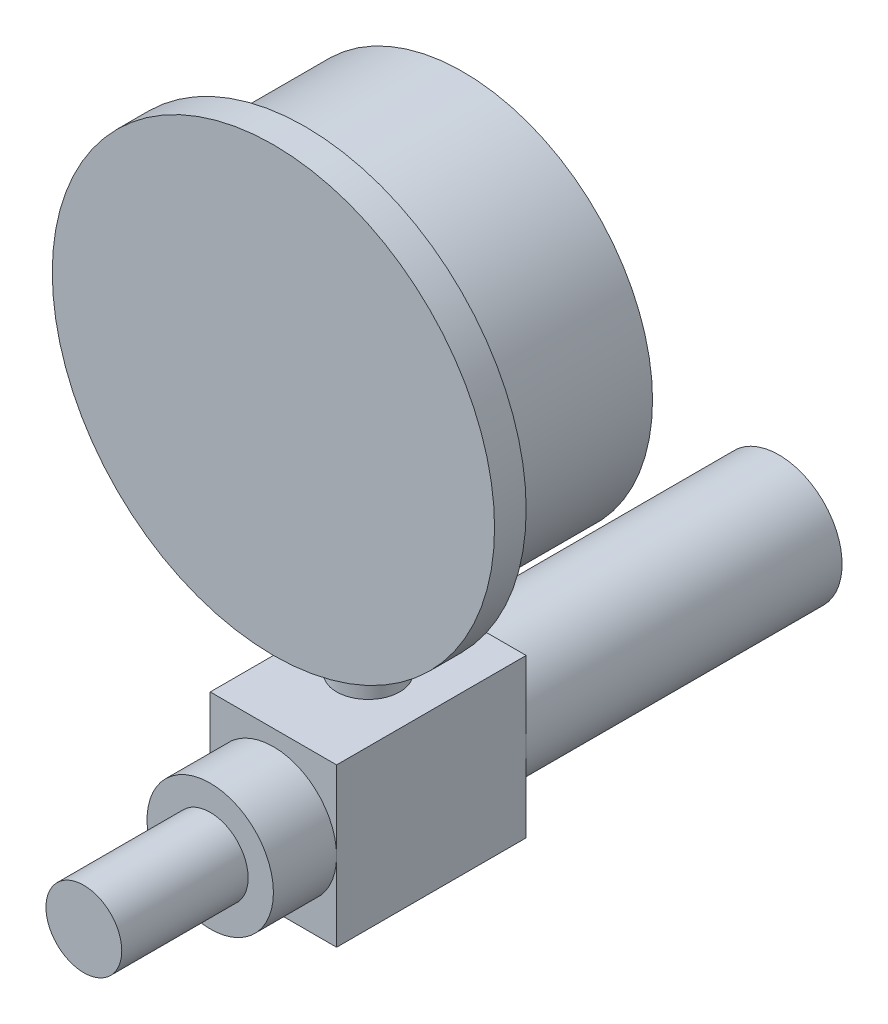
SolidWorks part; units mm, degrees
ref_plane "Alzado" through (0, 0, 0) normal (0, 0, 1) x (1, 0, 0)
ref_plane "Planta" through (0, 0, 0) normal (0, 1, 0) x (1, 0, 0)
ref_plane "Vista lateral" through (0, 0, 0) normal (1, 0, 0) x (0, 0, -1)
sketch "Croquis1" plane through (0, 0, 0) normal (0, 0, 1) x (1, 0, 0)
  line L0 (-35, 50) -> (35, 50) construction
  line L1 (35, 50) -> (35, -50) construction
  line L2 (35, -50) -> (-35, -50) construction
  line L3 (-35, -50) -> (-35, 50) construction
  line L4 (-35, 50) -> (35, -50) construction
  line L5 (-35, -50) -> (35, 50) construction
  line L7 (-10, -50) -> (10, -50)
  line L8 (-10, -50) -> (-10, -25)
  line L9 (-10, -25) -> (10, -25)
  line L10 (10, -50) -> (10, -25)
  circle A0 centre (0, 20) radius 30
  point P4 (0, 0)
  point P10 (0, -50)
  point P13 (0, 0)
  dimension "D5" = 60
  dimension "D1" = 70
  dimension "D2" = 100
  dimension "D3" = 20
  dimension "D4" = 25
extrude "Saliente-Extruir1" add sketch "Croquis1" against normal blind 30
sketch "Croquis2" plane through (0, 0, 0) normal (0, 0, 1) x (1, 0, 0)
  circle A0 centre (0, 20) radius 35
  circle A1 centre (0, 20) radius 30 construction
  circle A2 centre (0, 20) radius 30
  dimension "D1" = 70
  dimension "D2" = 60
extrude "Saliente-Extruir2" add sketch "Croquis2" against normal blind 5
sketch "Croquis3" plane through (0, -25, 0) normal (0, 1, 0) x (1, 0, 0)
  line L0 (10, 0) -> (-10, 0) construction
  line L1 (10, 30) -> (10, 0) construction
  circle A0 centre (0, 15) radius 5
  dimension "D2" = 10
  dimension "D3" = 10
  dimension "D1" = 15
extrude "Saliente-Extruir3" add sketch "Croquis3" along normal up to next
sketch "Croquis4" plane through (0, 0, 0) normal (0, 0, 1) x (1, 0, 0)
  line L0 (-10, -25) -> (10, -50) construction
  line L1 (10, -25) -> (-10, -50) construction
  circle A0 centre (0, -37.5) radius 10
  dimension "D1" = 20
extrude "Saliente-Extruir4" add sketch "Croquis4" along normal blind 10
sketch "Croquis5" plane through (0, 0, 10) normal (0, 0, 1) x (1, 0, 0)
  circle A0 centre (0, -37.5) radius 6
  circle A1 centre (0, -37.5) radius 10 construction
  dimension "D1" = 12
extrude "Saliente-Extruir5" add sketch "Croquis5" along normal blind 20
sketch "Croquis6" plane through (0, 0, -30) normal (0, 0, -1) x (-1, 0, 0)
  line L0 (-10, -25) -> (10, -50) construction
  line L1 (10, -50) -> (-10, -50) construction
  line L2 (-10, -50) -> (10, -25) construction
  circle A0 centre (0, -37.5) radius 10
  dimension "D1" = 20
sketch "Croquis8" plane through (10, 0, 0) normal (1, 0, 0) x (0, 0, -1)
extrude "Saliente-Extruir6" add sketch "Croquis6" along normal blind 50
